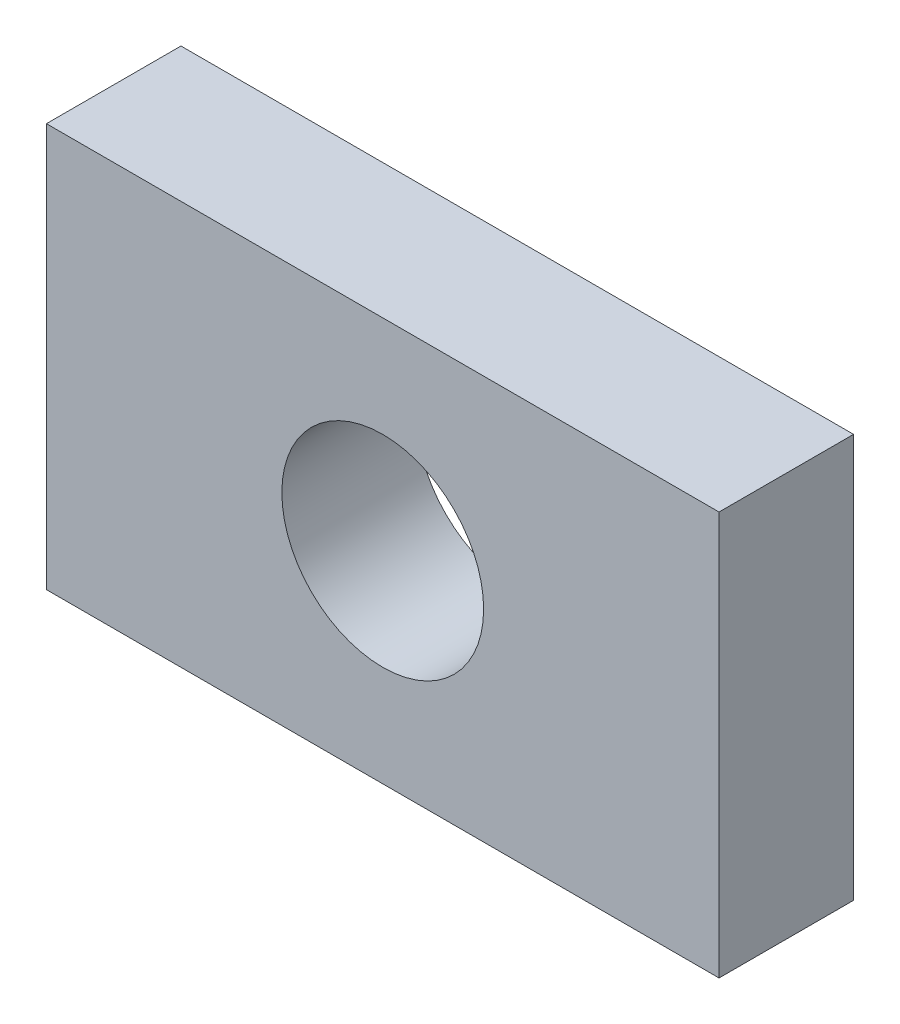
SolidWorks part; units mm, degrees
material "Acrylic (Medium-high impact)"
ref_plane "Front Plane" through (0, 0, 0) normal (0, 0, 1) x (1, 0, 0)
ref_plane "Top Plane" through (0, 0, 0) normal (0, 1, 0) x (1, 0, 0)
ref_plane "Right Plane" through (0, 0, 0) normal (1, 0, 0) x (0, 0, -1)
sketch "Model" plane through (0, 0, 0) normal (0, 0, 1) x (1, 0, 0)
  line L247 (2078.676, 1309.1383) -> (2078.676, 1303.1383)
  line L248 (2078.676, 1309.1383) -> (2088.676, 1309.1383)
  line L249 (2088.676, 1309.1383) -> (2088.676, 1303.1383)
  line L250 (2088.676, 1303.1383) -> (2078.676, 1303.1383)
  circle A76 centre (2083.676, 1306.1383) radius 1.5
extrude "Boss-Extrude1" add sketch "Model" along normal blind 2
